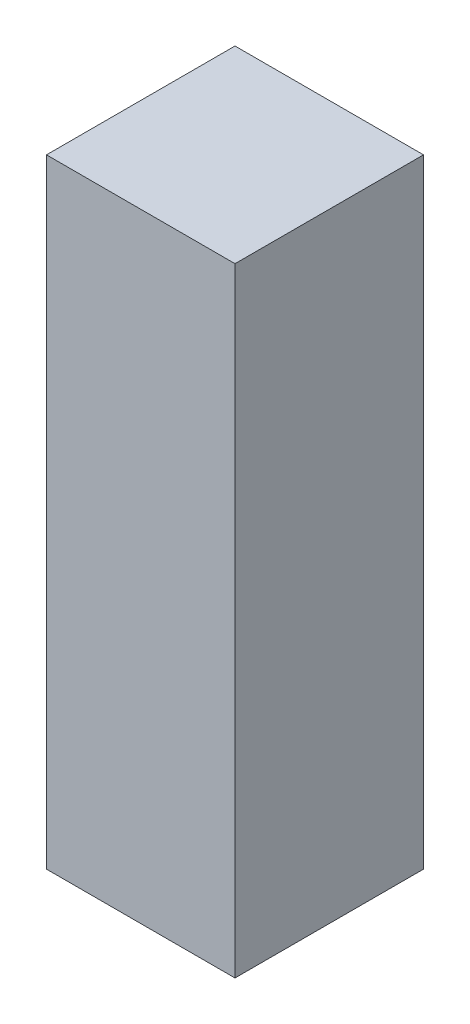
SolidWorks part; units mm, degrees
ref_plane "X-Y Datum" through (0, 0, 0) normal (0, 0, 1) x (1, 0, 0)
ref_plane "X-Z Datum" through (0, 0, 0) normal (0, 1, 0) x (1, 0, 0)
ref_plane "Y-Z Datum" through (0, 0, 0) normal (1, 0, 0) x (0, 0, -1)
sketch "Sketch1" plane through (0, 0, 0) normal (0, 1, 0) x (1, 0, 0)
  line L1 (0, 0) -> (71, 0)
  line L2 (0, 0) -> (0, 71)
  line L3 (0, 71) -> (71, 71)
  line L4 (71, 0) -> (71, 71)
extrude "Boss-Extrude1" add sketch "Sketch1" along normal blind 233
